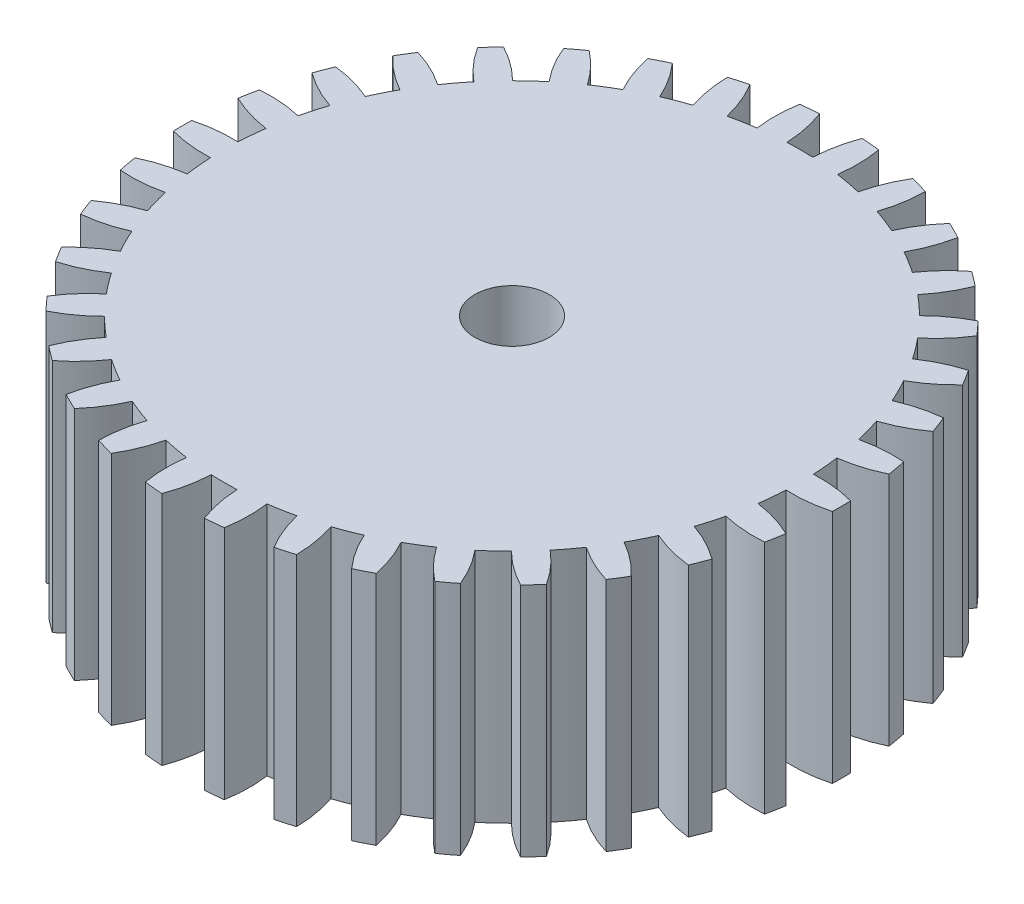
SolidWorks part; units mm, degrees
ref_plane "Front Plane" through (0, 0, 0) normal (0, 0, 1) x (1, 0, 0)
ref_plane "Top Plane" through (0, 0, 0) normal (0, 1, 0) x (1, 0, 0)
ref_plane "Right Plane" through (0, 0, 0) normal (1, 0, 0) x (0, 0, -1)
sketch "Sketch1" plane through (0, 0, 0) normal (0, 1, 0) x (1, 0, 0)
  circle A0 centre (0, 0) radius 13.5001
  dimension "D1" = 27.0002
extrude "Boss-Extrude1" add sketch "Sketch1" along normal blind 9.652 contours A0
sketch "Sketch2" plane through (0, 9.652, 0) normal (0, 1, 0) x (1, 0, 0)
  line L0 (0, 0) -> (0, 18.3647) construction
  line L1 (1.1173, 14.0322) -> (-1.1173, 14.0322)
  line L2 (0, 0) -> (0.8213, 18.322) construction
  circle A0 centre (0, 0) radius 12.7508 construction
  arc A1 (0.5285, 11.7899) -> (-0.5285, 11.7899) centre (0, 0) ccw
  arc A4 (0.5285, 11.7899) -> (1.1173, 14.0322) centre (6.0317, 11.5432) cw
  arc A5 (-0.5285, 11.7899) -> (-1.1173, 14.0322) centre (-6.0317, 11.5432) ccw
  point P13 (0, 14.0322)
  dimension "D2" = 2.567
extrude "Cut-Extrude1" cut sketch "Sketch2" against normal through all both and the other way through all
sketch "Sketch3" plane through (0, 0, 0) normal (0, 1, 0) x (1, 0, 0)
  circle A0 centre (0, 0) radius 1.524
  dimension "D1" = 3.048
extrude "Cut-Extrude2" cut sketch "Sketch3" along normal through all both and the other way through all contours A0
pattern_circular "CirPattern1" count 34 over 360 about axis through (0, 0, 0) along (0, 1, 0) of "Cut-Extrude1"
